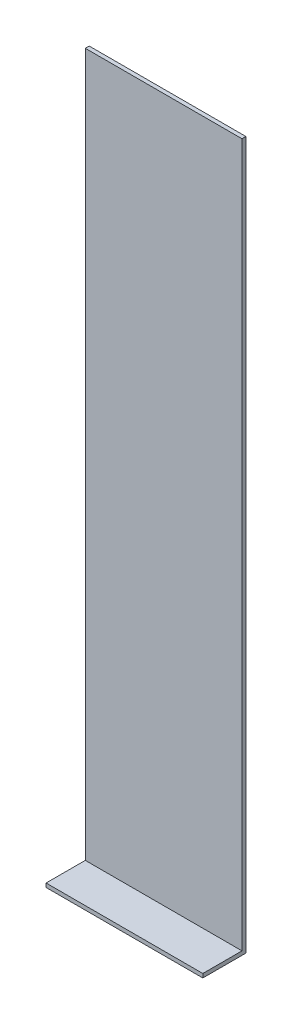
SolidWorks part; units mm, degrees
material "AISI 4340 Steel, annealed"
ref_plane "Front Plane" through (0, 0, 0) normal (0, 0, 1) x (1, 0, 0)
ref_plane "Top Plane" through (0, 0, 0) normal (0, 1, 0) x (1, 0, 0)
ref_plane "Right Plane" through (0, 0, 0) normal (1, 0, 0) x (0, 0, -1)
sketch "Sketch1" plane through (0, 0, 0) normal (1, 0, 0) x (0, 0, -1)
  line L0 (0, 0) -> (-100, 0)
  line L1 (-100, 0) -> (-100, -10)
  line L2 (-100, -10) -> (10, -10)
  line L3 (10, -10) -> (10, 1795.07)
  line L4 (10, 1795.07) -> (0, 1795.07)
  line L5 (0, 1795.07) -> (0, 0)
  dimension "D1" = 1805.07
  dimension "D2" = 10
  dimension "D3" = 10
  dimension "D4" = 100
extrude "Boss-Extrude1" add sketch "Sketch1" along normal mid plane 400
